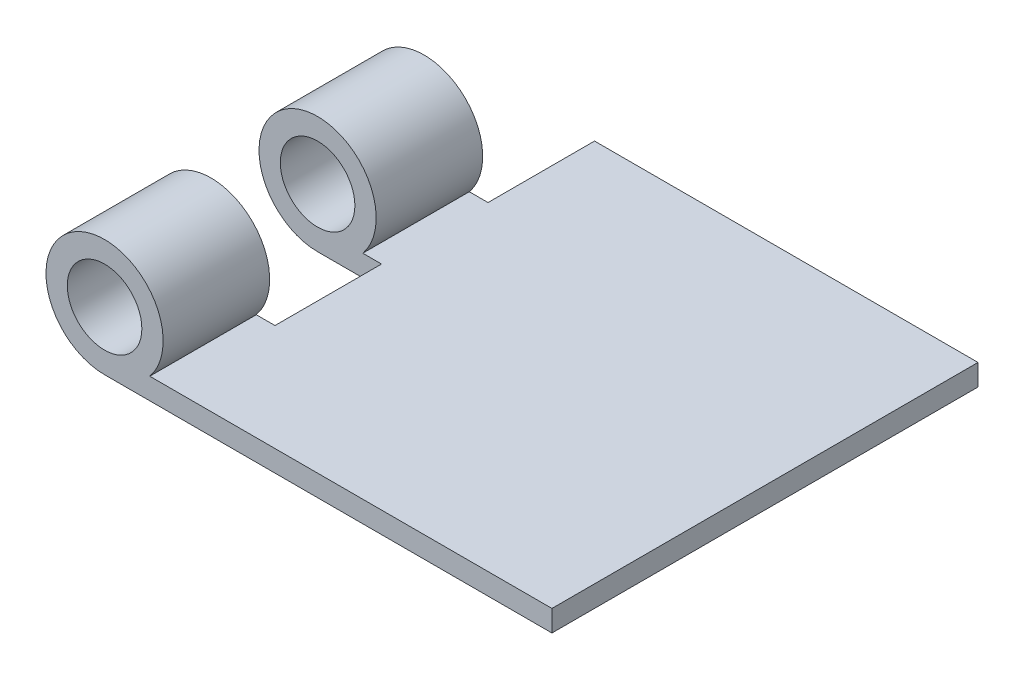
SolidWorks part; units mm, degrees
material "Nylon 6/10"
ref_plane "Front Plane" through (0, 0, 0) normal (0, 0, 1) x (1, 0, 0)
ref_plane "Top Plane" through (0, 0, 0) normal (0, 1, 0) x (1, 0, 0)
ref_plane "Right Plane" through (0, 0, 0) normal (1, 0, 0) x (0, 0, -1)
sketch "Sketch1" plane through (0, 0, 0) normal (0, 1, 0) x (1, 0, 0)
  line L3 (18, 26.4537) -> (18, 5) construction
  line L4 (18, 10) -> (18, 5)
  line L5 (18, 5) -> (15, 5)
  line L6 (15, 5) -> (15, 0)
  line L7 (15, 0) -> (18, 0)
  line L8 (18, 0) -> (18, -5)
  line L9 (18, -5) -> (15, -5)
  line L10 (15, -5) -> (15, -10)
  line L11 (18, 0) -> (18, -5) construction
  line L12 (18, 10) -> (36, 10)
  line L13 (36, 10) -> (36, -10)
  line L14 (36, -10) -> (15, -10)
  dimension "D1" = 36
  dimension "D2" = 20
  dimension "D3" = 10
  dimension "D4" = 18
  dimension "D5" = 3
  dimension "D6" = 5
  dimension "D7" = 3
  dimension "D8" = 5
  dimension "D9" = 10
extrude "Boss-Extrude1" add sketch "Sketch1" against normal blind 1
sketch "Sketch2" plane through (0, 0, 10) normal (0, 0, 1) x (1, 0, 0)
  line L0 (15, -1) -> (36, -1) construction
  circle A0 centre (15, 1.75) radius 2.75
  circle A1 centre (15, 1.75) radius 1.75
  dimension "D1" = 5.5
  dimension "D2" = 1
extrude "Boss-Extrude2" add sketch "Sketch2" against normal up to surface (5 mm away) up to face at (16.5, -0.5, 5)
sketch "Sketch3" plane through (0, 0, -5) normal (0, 0, -1) x (-1, 0, 0)
  line L0 (-36, -1) -> (-18, -1) construction
  circle A0 centre (-15, 1.75) radius 2.75
  circle A1 centre (-15, 1.75) radius 1.75
  dimension "D1" = 1
extrude "Boss-Extrude3" add sketch "Sketch3" against normal up to surface (5 mm away) up to face at (16.5, -0.5, 0)
